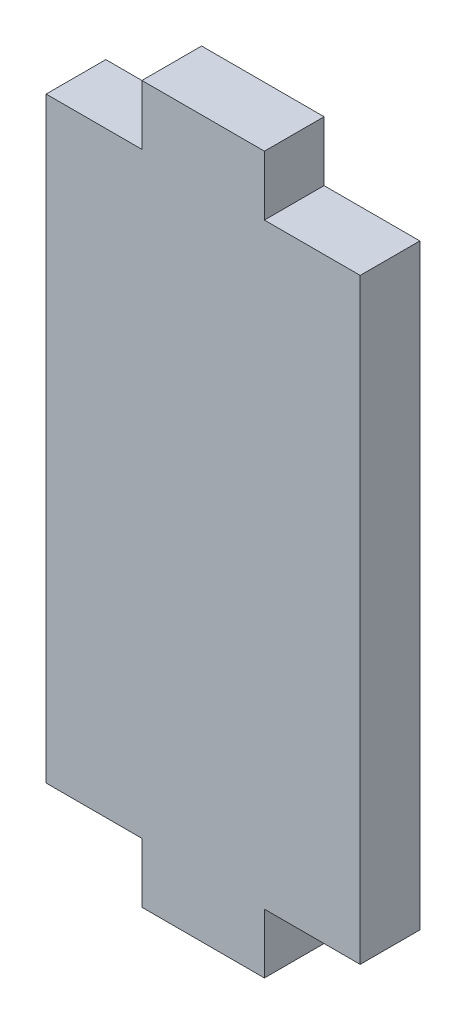
SolidWorks part; units mm, degrees
ref_plane "Front Plane" through (0, 0, 0) normal (0, 0, 1) x (1, 0, 0)
ref_plane "Top Plane" through (0, 0, 0) normal (0, 1, 0) x (1, 0, 0)
ref_plane "Right Plane" through (0, 0, 0) normal (1, 0, 0) x (0, 0, -1)
sketch "Sketch1" plane through (0, 0, 0) normal (0, 0, 1) x (1, 0, 0)
  line L1 (0, 0) -> (25.4, 0)
  line L2 (0, 0) -> (0, 57.912)
  line L3 (0, 57.912) -> (25.4, 57.912)
  line L4 (25.4, 0) -> (25.4, 57.912)
  dimension "D1" = 57.912
  dimension "D2" = 25.4
extrude "Boss-Extrude1" add sketch "Sketch1" along normal blind 4.826
sketch "Sketch2" plane through (0, 0, 4.826) normal (0, 0, 1) x (1, 0, 0)
  line L0 (25.4, 57.912) -> (0, 57.912) construction
  line L1 (7.747, 57.912) -> (17.653, 57.912)
  line L2 (7.747, 57.912) -> (7.747, 53.086)
  line L3 (7.747, 53.086) -> (17.653, 53.086)
  line L4 (17.653, 57.912) -> (17.653, 53.086)
  line L5 (12.7, 53.086) -> (12.7, 57.912) construction
  line L6 (0, 57.912) -> (0, 0) construction
  line L7 (25.4, 0) -> (25.4, 57.912) construction
  line L8 (0, 57.912) -> (7.747, 57.912)
  line L9 (0, 57.912) -> (0, 53.086)
  line L10 (0, 53.086) -> (7.747, 53.086)
  line L11 (7.747, 57.912) -> (7.747, 53.086)
  line L12 (17.653, 57.912) -> (25.4, 57.912)
  line L13 (17.653, 57.912) -> (17.653, 53.086)
  line L14 (17.653, 53.086) -> (25.4, 53.086)
  line L15 (25.4, 57.912) -> (25.4, 53.086)
  line L16 (0, 28.956) -> (25.4, 28.956) construction
  line L17 (12.7, 4.826) -> (12.7, 0) construction
  line L18 (25.4, 0) -> (25.4, 4.826)
  line L19 (17.653, 4.826) -> (25.4, 4.826)
  line L20 (17.653, 0) -> (17.653, 4.826)
  line L21 (17.653, 0) -> (25.4, 0)
  line L22 (7.747, 0) -> (7.747, 4.826)
  line L23 (0, 4.826) -> (7.747, 4.826)
  line L24 (0, 0) -> (0, 4.826)
  line L25 (0, 0) -> (7.747, 0)
  line L26 (17.653, 0) -> (17.653, 4.826)
  line L27 (7.747, 4.826) -> (17.653, 4.826)
  line L28 (7.747, 0) -> (7.747, 4.826)
  line L29 (7.747, 0) -> (17.653, 0)
  line L30 (12.7, 53.086) -> (12.7, 57.912) construction
  line M13 (0, 57.912) -> (0, 0)
  line M14 (0, 0) -> (25.4, 0)
  line M15 (25.4, 0) -> (25.4, 57.912)
  line M16 (25.4, 57.912) -> (0, 57.912)
  dimension "D1" = 9.906
  dimension "D2" = 4.826
  dimension "D3" = 12.7
extrude "Cut-Extrude1" cut sketch "Sketch2" against normal through all contours L4 L14 M15 M16 | L10 L2 M13 M16 | L20 L19 M14 M15 | L23 L22 M13 M14
equation "\"MDF\"= 0.19in"
equation "\"PVCID\" = 2.067in"
equation "\"PVCOD\" = 2.375in"
equation "\"GenDiameter\"= 60mm"
equation "\"GenCutDiameter\" = 1.8in"
equation "\"GenCutDistance\" = 1"
equation "\"TowerHeight\" = 6in"
equation "\"TowerFrontBase\" = 3in"
equation "\"FunnelHeight\" = 1in"
equation "\"FunnelAngle\" = 20"
equation "\"TowerSideBase\" = 3in"
equation "\"TowerPanelLength\" = 2in"
equation "\"TowerPanelLeeway\" = 0.5in"
equation "\"BaseLength\" = 9in"
equation "\"BaseWidth\" = 10in"
equation "\"WheelHoleLength\" = 3.25in"
equation "\"WheelHoleWidth\" = 26mm"
equation "\"WheelHoleFromBack\" = 1.5in"
equation "\"DropLength\" = 1in"
equation "\"DropWidth\" = 8.5in"
equation "\"BumperWidth\" = 1in"
equation "\"SmallHexDiameter\" = 0.185in"
equation "\"SmallHexHeight\" = 0.701in"
equation "\"ScrewSize\" = 0.106in"
equation "\"BigHexDiameter\" = 0.251in"
equation "\"BigHexHeight\" = 0.374in"
equation "\"PCBThickness\" = 0.066in"
equation "\"ConnectorHeight\" = 0.517in"
equation "\"BoardHeight\" = 0.583in"
equation "\"UnoStackHeight\" = 1.351in"
equation "\"UnoStackWidth\" = 3.053in"
equation "\"UnoStackLength\" = 3.152in"
equation "\"HBridgeWidth\" = 1.797in"
equation "\"HBridgeLength\" = 2.236in"
equation "\"DSWidth\" = 1.820in"
equation "\"DSLength\" = 1.833in"
equation "\"StepperWidth\" = 1.799in"
equation "\"StepperLength\" = 2.248in"
equation "\"ULNWidth\" = 1.304in"
equation "\"ULNLength\" = 1.545in"
equation "\"VSwitchHeight\" = 0.392in"
equation "\"VSwitchWidth\" = 0.637in"
equation "\"VSwitchLength\" = 1.097in"
equation "\"SkateWheelDiameter\" = 80mm"
equation "\"SkateWheelThickness\" = 24mm"
equation "\"BaseDistance\" = 3in"
equation "\"DummyVar\" = 2in"
equation "\"D1@Sketch1\"=2*\"MDF\"+1.9in"
equation "\"D1@Boss-Extrude1\"=\"MDF\""
equation "\"D2@Sketch2\"=\"MDF\""
